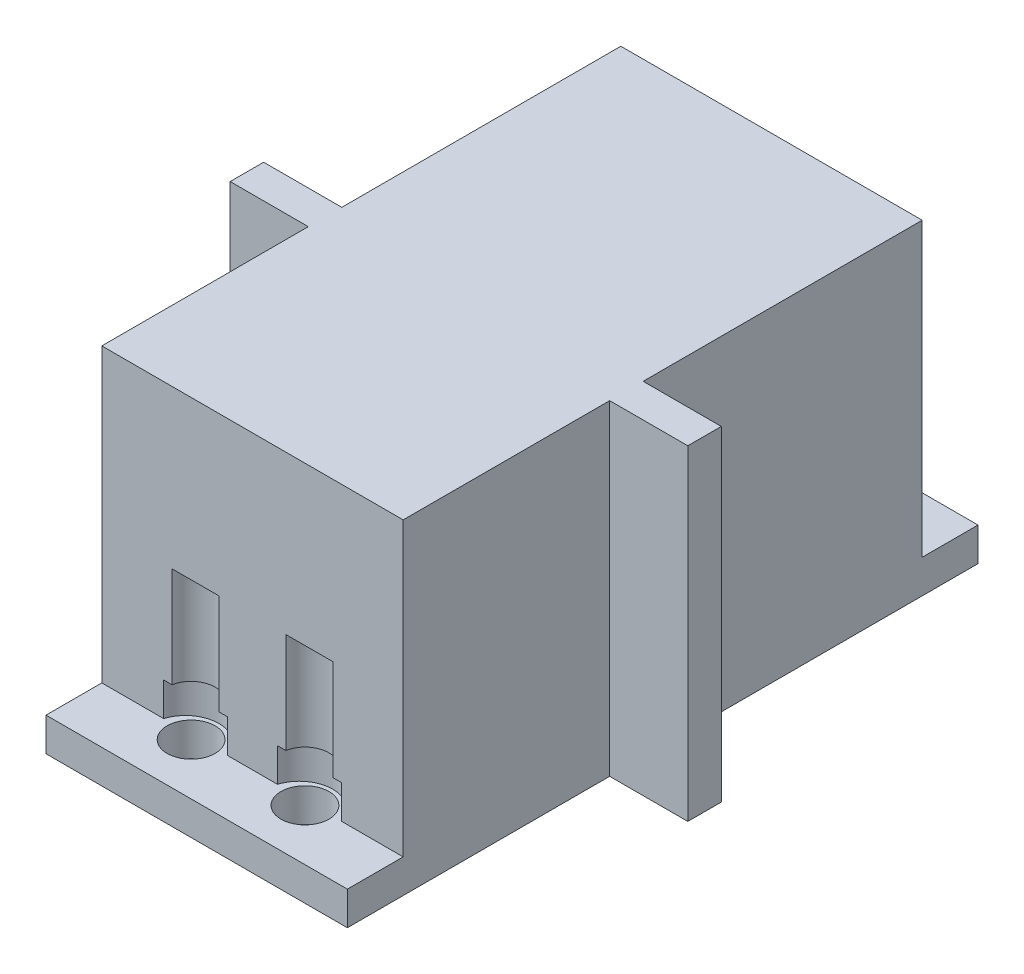
SolidWorks part; units mm, degrees
ref_plane "Front Plane" through (0, 0, 0) normal (0, 0, 1) x (1, 0, 0)
ref_plane "Top Plane" through (0, 0, 0) normal (0, 1, 0) x (1, 0, 0)
ref_plane "Right Plane" through (0, 0, 0) normal (1, 0, 0) x (0, 0, -1)
sketch "Sketch1" plane through (0, 0, 0) normal (0, 0, 1) x (1, 0, 0)
  line L0 (30.8969, -36.546) -> (30.8969, -5.546) construction
  line L3 (7.3969, -30.546) -> (34.3969, -30.546)
  line L5 (34.3969, -30.546) -> (34.3969, -3.046)
  line L6 (10.8969, -36.546) -> (10.8969, -5.546) construction
  line L7 (7.3969, -30.546) -> (7.3969, -3.046)
  line L9 (7.3969, -1.396) -> (34.3969, -1.396)
  line L11 (7.3969, -1.396) -> (7.3969, -3.046)
  line L12 (34.3969, -3.046) -> (34.3969, -1.396)
  dimension "D1" = 3.5
  dimension "D2" = 3.5
extrude "Boss-Extrude1" add sketch "Sketch1" along normal blind 3
sketch "Sketch2" plane through (0, 0, 0) normal (0, 0, -1) x (-1, 0, 0)
  line L0 (-7.3969, -30.546) -> (-34.3969, -30.546) construction
  line L1 (-34.3969, -30.546) -> (-7.3969, -30.546)
  line L2 (-34.3969, -30.546) -> (-34.3969, -27.546)
  line L3 (-34.3969, -27.546) -> (-7.3969, -27.546)
  line L4 (-7.3969, -30.546) -> (-7.3969, -27.546)
  line L9 (-34.3969, -30.546) -> (-34.3969, -1.396) construction
  line L10 (-7.3969, -1.396) -> (-7.3969, -30.546) construction
  dimension "D1" = 3
extrude "Boss-Extrude2" add sketch "Sketch2" along normal blind 5
sketch "Sketch3" plane through (0, -30.546, 0) normal (0, -1, 0) x (1, 0, 0)
  circle A0 centre (15.7969, -0.9) radius 2.15
  circle A1 centre (25.9969, -0.9) radius 2.15
extrude "Cut-Extrude1" cut sketch "Sketch3" against normal blind 15
sketch "Sketch5" plane through (0, -27.546, 0) normal (0, 1, 0) x (1, 0, 0)
  circle A0 centre (15.7969, 0.9) radius 3
  circle A1 centre (25.9969, 0.9) radius 3
  dimension "D1" = 6
  dimension "D2" = 6
extrude "Cut-Extrude3" cut sketch "Sketch5" along normal blind 3
sketch "Sketch7" plane through (0, 0, 3) normal (0, 0, 1) x (1, 0, 0)
  line L0 (7.3969, -30.546) -> (34.3969, -30.546) construction
  line L1 (9.3969, -1.396) -> (7.3969, -1.396)
  line L2 (9.3969, -1.396) -> (9.3969, -30.546)
  line L3 (9.3969, -30.546) -> (7.3969, -30.546)
  line L4 (7.3969, -1.396) -> (7.3969, -30.546)
  line L5 (34.3969, -1.396) -> (7.3969, -1.396) construction
  line L6 (7.3969, -1.396) -> (7.3969, -30.546) construction
  dimension "D1" = 2
extrude "Boss-Extrude6" add sketch "Sketch7" along normal blind 43.5
sketch "Sketch8" plane through (9.3969, 0, 0) normal (1, 0, 0) x (0, 0, -1)
  line L1 (-43.5, -30.546) -> (-46.5, -30.546)
  line L2 (-43.5, -30.546) -> (-43.5, -1.396)
  line L3 (-43.5, -1.396) -> (-46.5, -1.396)
  line L4 (-46.5, -30.546) -> (-46.5, -1.396)
  line L5 (-46.5, -30.546) -> (-3, -30.546) construction
  line L10 (-46.5, -1.396) -> (-3, -1.396) construction
  line L11 (-43, -30.546) -> (-43, -5.546) construction
  dimension "D1" = 0.5
  dimension "D2" = 3
extrude "Boss-Extrude7" add sketch "Sketch8" along normal up to surface (25 mm away) up to face at (34.3969, -19.8293, -0.6667)
sketch "Sketch9" plane through (0, 0, 46.5) normal (0, 0, 1) x (1, 0, 0)
  line L0 (34.3969, -30.546) -> (34.3969, -1.396) construction
  line L1 (34.3969, -30.546) -> (7.3969, -30.546)
  line L2 (34.3969, -30.546) -> (34.3969, -27.546)
  line L3 (34.3969, -27.546) -> (7.3969, -27.546)
  line L4 (7.3969, -30.546) -> (7.3969, -27.546)
  line L5 (7.3969, -30.546) -> (34.3969, -30.546) construction
  line L6 (7.3969, -1.396) -> (7.3969, -30.546) construction
  dimension "D1" = 3
extrude "Boss-Extrude8" add sketch "Sketch9" along normal blind 5
sketch "Sketch10" plane through (0, -30.546, 0) normal (0, -1, 0) x (1, 0, 0)
  circle A0 centre (25.9969, 46.9) radius 2.15
  circle A1 centre (15.7969, 46.9) radius 2.15
extrude "Cut-Extrude4" cut sketch "Sketch10" against normal blind 15
ref_plane "Plane1" through (0, 0, 23.25) normal (0, 0, -1) x (-1, 0, 0)
mirror "Mirror1" about plane through (0, 0, 23.25) normal (0, 0, -1) of "Cut-Extrude3"
ref_plane "Plane2" through (20.8969, 0, 0) normal (-1, 0, 0) x (0, 0, 1)
mirror "Mirror2" about plane through (20.8969, 0, 0) normal (-1, 0, 0) of "Boss-Extrude6"
sketch "Sketch11" plane through (32.3969, 0, 0) normal (-1, 0, 0) x (0, 0, 1)
  line L1 (43.5, -2.396) -> (3, -2.396)
  line L2 (43.5, -2.396) -> (43.5, -1.396)
  line L3 (43.5, -1.396) -> (3, -1.396)
  line L4 (3, -2.396) -> (3, -1.396)
  line L5 (43.5, -1.396) -> (43.5, -30.546) construction
  line L6 (3, -30.546) -> (3, -1.396) construction
  line L7 (43.5, -1.396) -> (3, -1.396) construction
  dimension "D1" = 1
extrude "Boss-Extrude9" add sketch "Sketch11" along normal up to surface (23 mm away) up to face at (9.3969, -15.971, 23.25)
sketch "Sketch12" plane through (34.3969, 0, 0) normal (1, 0, 0) x (0, 0, -1)
  line L0 (-28, -1.396) -> (-28, -63.5273) construction
  line L1 (-25, -1.396) -> (-28, -1.396)
  line L2 (-25, -1.396) -> (-25, -30.546)
  line L3 (-25, -30.546) -> (-28, -30.546)
  line L4 (-28, -1.396) -> (-28, -30.546)
  line L5 (-46.5, -1.396) -> (0, -1.396) construction
  line L6 (-51.5, -30.546) -> (5, -30.546) construction
  dimension "D1" = 3
extrude "Boss-Extrude10" add sketch "Sketch12" along normal blind 7
mirror "Mirror3" about plane through (20.8969, 0, 0) normal (-1, 0, 0) of "Boss-Extrude10"
